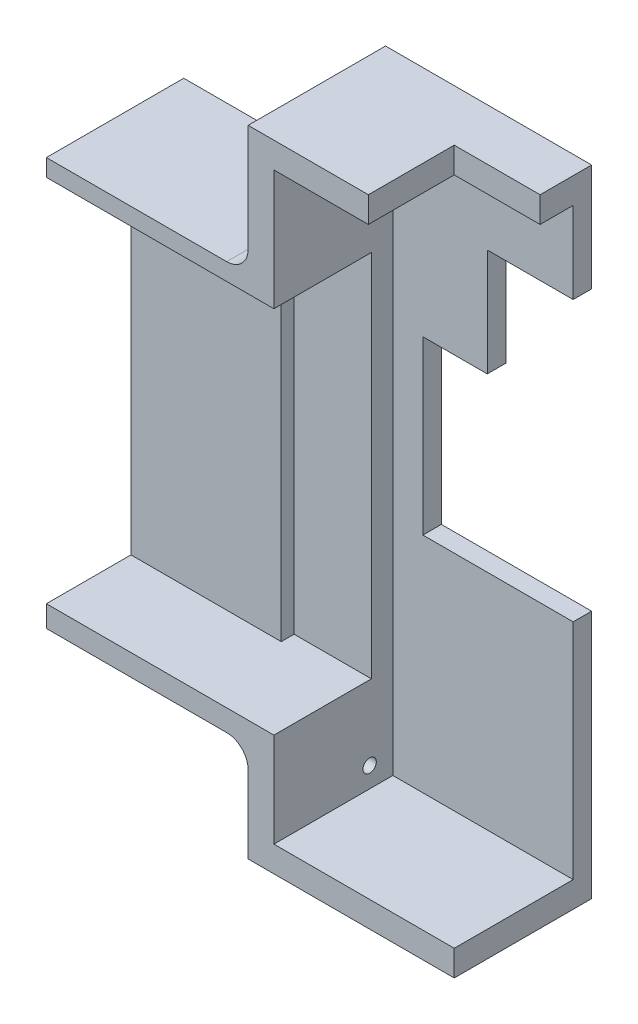
SolidWorks part; units mm, degrees
material "ABS"
ref_plane "前视基准面" through (0, 0, 0) normal (0, 0, 1) x (1, 0, 0)
ref_plane "上视基准面" through (0, 0, 0) normal (0, 1, 0) x (1, 0, 0)
ref_plane "右视基准面" through (0, 0, 0) normal (1, 0, 0) x (0, 0, -1)
sketch "草图1" plane through (0, 0, 0) normal (0, 1, 0) x (1, 0, 0)
  line L1 (-65, -32) -> (65, -32)
  line L2 (-65, -32) -> (-65, 32)
  line L3 (-65, 32) -> (65, 32)
  line L4 (65, -32) -> (65, 32)
  line L5 (-65, -32) -> (65, 32) construction
  line L6 (-65, 32) -> (65, -32) construction
  point P0 (0, 0)
  dimension "D1" = 64
  dimension "D2" = 130
extrude "凸台-拉伸1" add sketch "草图1" along normal blind 125
sketch "草图2" plane through (65, 0, 0) normal (1, 0, 0) x (0, 0, -1)
  line L0 (0, 0) -> (0, 39.3127) construction
  line L1 (-27.7, 5) -> (27.7, 5)
  line L2 (-27.7, 5) -> (-27.7, 119)
  line L3 (-27.7, 119) -> (27.7, 119)
  line L4 (27.7, 5) -> (27.7, 119)
  line L5 (-32, 0) -> (32, 0) construction
  dimension "D1" = 55.4
  dimension "D2" = 114
  dimension "D3" = 5
extrude "切除-拉伸1" cut sketch "草图2" against normal blind 47
sketch "草图3" plane through (18, 0, 0) normal (1, 0, 0) x (0, 0, -1)
  line L0 (-27.7, 5) -> (27.7, 5) construction
  line L1 (-22.7, 91) -> (22.7, 91)
  line L2 (-22.7, 91) -> (-22.7, 5)
  line L3 (-22.7, 5) -> (22.7, 5)
  line L4 (22.7, 91) -> (22.7, 5)
  line L5 (0, 0) -> (0, 26.028) construction
  line L6 (27.7, 119) -> (-27.7, 119) construction
  dimension "D1" = 28
  dimension "D2" = 45.4
extrude "切除-拉伸2" cut sketch "草图3" against normal blind 78
sketch "草图4" plane through (65, 0, 0) normal (1, 0, 0) x (0, 0, -1)
  line L0 (-32, 0) -> (32, 0) construction
  line L1 (14.5499, 75) -> (38.5888, 75)
  line L2 (14.5499, 75) -> (14.5499, 35)
  line L3 (14.5499, 35) -> (38.5888, 35)
  line L4 (38.5888, 75) -> (38.5888, 35)
  dimension "D1" = 35
  dimension "D2" = 40
extrude "切除-拉伸3" cut sketch "草图4" against normal blind 40
sketch "草图5" plane through (65, 0, 0) normal (1, 0, 0) x (0, 0, -1)
  line L0 (32, 125) -> (32, 75) construction
  line L1 (27.7, 75) -> (32, 75)
  line L2 (27.7, 75) -> (27.7, 100)
  line L3 (27.7, 100) -> (32, 100)
  line L4 (32, 75) -> (32, 100)
  line L5 (27.7, 5) -> (27.7, 119) construction
  line L6 (-32, 125) -> (32, 125) construction
  point P7 (0, 0)
  dimension "D1" = 25
  dimension "D2" = 25
extrude "切除-拉伸4" cut sketch "草图5" against normal blind 25
sketch "草图6" plane through (0, 125, 0) normal (0, 1, 0) x (1, 0, 0)
  line L0 (0, 0) -> (40.4194, 0) construction
  line L1 (50, 20) -> (40, 20)
  line L2 (50, 20) -> (50, -20)
  line L3 (50, -20) -> (40, -20)
  line L4 (40, 20) -> (40, -20)
  line L5 (65, -32) -> (65, 32) construction
  dimension "D1" = 40
  dimension "D2" = 10
  dimension "D3" = 15
extrude "切除-拉伸5" cut sketch "草图6" against normal blind 25
sketch "草图9" plane through (0, 0, 32) normal (0, 0, 1) x (1, 0, 0)
  line L0 (-65, 125) -> (65, 125) construction
  line L1 (60, 125) -> (65, 125)
  line L2 (60, 125) -> (60, 0)
  line L3 (60, 0) -> (65, 0)
  line L4 (65, 125) -> (65, 0)
  dimension "D1" = 5
extrude "切除-拉伸8" cut sketch "草图9" against normal through all
sketch "草图12" plane through (0, 0, 32) normal (0, 0, 1) x (1, 0, 0)
  line L1 (-65, 125) -> (-33, 125)
  line L2 (-65, 125) -> (-65, 95)
  line L3 (-65, 95) -> (-33, 95)
  line L4 (-33, 125) -> (-33, 95)
  dimension "D1" = 30
  dimension "D2" = 32
extrude "切除-拉伸10" cut sketch "草图12" against normal through all
sketch "草图13" plane through (0, 125, 0) normal (0, 1, 0) x (1, 0, 0)
  line L0 (60, 32) -> (-33, 32) construction
  line L1 (-33, -32) -> (12, -32)
  line L2 (-33, -32) -> (-33, 32)
  line L3 (-33, 32) -> (12, 32)
  line L4 (12, -32) -> (12, 32)
  dimension "D2" = 45
extrude "切除-拉伸11" cut sketch "草图13" against normal blind 30
sketch "草图14" plane through (-65, 0, 0) normal (-1, 0, 0) x (0, 0, 1)
  line L1 (32, 0) -> (0, 0)
  line L2 (32, 0) -> (32, 157.4826)
  line L3 (32, 157.4826) -> (0, 157.4826)
  line L4 (0, 0) -> (0, 157.4826)
  line L5 (-32, 0) -> (32, 0) construction
extrude "切除-拉伸12" cut sketch "草图14" against normal through all
sketch "草图15" plane through (0, 0, 0) normal (0, 0, 1) x (1, 0, 0)
  line L0 (18, 91) -> (-60, 91) construction
  line L1 (18, 5) -> (18, 119) construction
  line L2 (60, 0) -> (-65, 0) construction
  line L4 (-65, 95) -> (-65, 0) construction
  circle A0 centre (15, 94) radius 2
  circle A1 centre (-58, 2.5) radius 1.5
  dimension "D1" = 4
  dimension "D2" = 3
  dimension "D3" = 3
  dimension "D4" = 3
  dimension "D5" = 2.5
  dimension "D6" = 7
extrude "凸台-拉伸3" [suppressed] add sketch "草图15" along normal blind 6
chamfer "倒角1" [suppressed] distance 0.5 angle 45
sketch "草图18" plane through (0, 0, 0) normal (0, 0, 1) x (1, 0, 0)
  line L0 (-65, 95) -> (12, 95) construction
  line L1 (-35, 95) -> (-65, 95)
  line L2 (-35, 95) -> (-35, 0)
  line L3 (-35, 0) -> (-65, 0)
  line L4 (-65, 95) -> (-65, 0)
  line L5 (-65, 95) -> (-65, 0) construction
  dimension "D1" = 30
extrude "切除-拉伸15" cut sketch "草图18" against normal through all
sketch "草图19" plane through (0, 0, -22.7) normal (0, 0, 1) x (1, 0, 0)
  line L0 (-35, 5) -> (60, 5) construction
  line L1 (-35, 91) -> (0, 91)
  line L2 (-35, 91) -> (-35, 5)
  line L3 (-35, 5) -> (0, 5)
  line L4 (0, 91) -> (0, 5)
  dimension "D1" = 35
extrude "凸台-拉伸4" add sketch "草图19" along normal blind 3
sketch "草图20" plane through (40, 0, 0) normal (1, 0, 0) x (0, 0, -1)
  line L4 (20, 125) -> (0, 125)
  line L5 (0, 119) -> (20, 119)
  line L7 (20, 119) -> (20, 125)
  line L8 (20, 125) -> (0, 125)
  line L11 (20, 119) -> (20, 125)
  line L12 (0, 119) -> (20, 119)
  line L17 (0, 125) -> (0, 119)
  line L19 (0, 125) -> (0, 119)
  dimension "D1" = 0
extrude "切除-拉伸16" cut sketch "草图20" along normal through all
fillet "圆角1" radius 5 1 edges at (12, 95, -16)
sketch "草图21" plane through (0, 5, 0) normal (0, 1, 0) x (1, 0, 0)
  line L1 (18, 27.7) -> (60, 27.7)
  line L2 (18, 27.7) -> (18, 0)
  line L3 (18, 0) -> (60, 0)
  line L4 (60, 27.7) -> (60, 0)
extrude "切除-拉伸17" cut sketch "草图21" against normal through all
sketch "草图22" plane through (0, 0, 0) normal (0, 0, 1) x (1, 0, 0)
  line L0 (12, 0) -> (18, 0)
  line L1 (18, 0) -> (-35, 0) construction
  line L2 (18, 0) -> (18, -17)
  line L3 (18, -17) -> (60, -17)
  line L4 (60, -17) -> (60, -23)
  line L5 (60, -23) -> (12, -23)
  line L6 (12, -23) -> (12, 0)
  line L7 (60, 0) -> (60, 35) construction
  point P5 (0, 0)
  dimension "D1" = 6
  dimension "D2" = 6
  dimension "D3" = 17
extrude "凸台-拉伸7" add sketch "草图22" against normal up to surface (27.7 mm away) up to face at (40.6, 65.8, -27.7)
sketch "草图23" plane through (0, 0, 0) normal (0, -1, 0) x (1, 0, 0)
  line L1 (60, -32) -> (12, -32)
  line L2 (60, -32) -> (60, -27.7)
  line L3 (60, -27.7) -> (12, -27.7)
  line L4 (12, -32) -> (12, -27.7)
extrude "凸台-拉伸8" add sketch "草图23" along normal up to surface (23 mm away) up to face at (36, -23, -13.85)
sketch "草图25" plane through (12, 0, 0) normal (-1, 0, 0) x (0, 0, 1)
  circle A0 centre (-22.3, 113.3) radius 1.55 construction
  circle A1 centre (-22.3, -12.3) radius 1.55 construction
  circle A2 centre (-22.3, 113.3) radius 1.55
  circle A3 centre (-22.3, -12.3) radius 1.55
extrude "切除-拉伸19" cut sketch "草图25" against normal through all
fillet "圆角3" radius 5 1 edges at (12, 0, -16)
